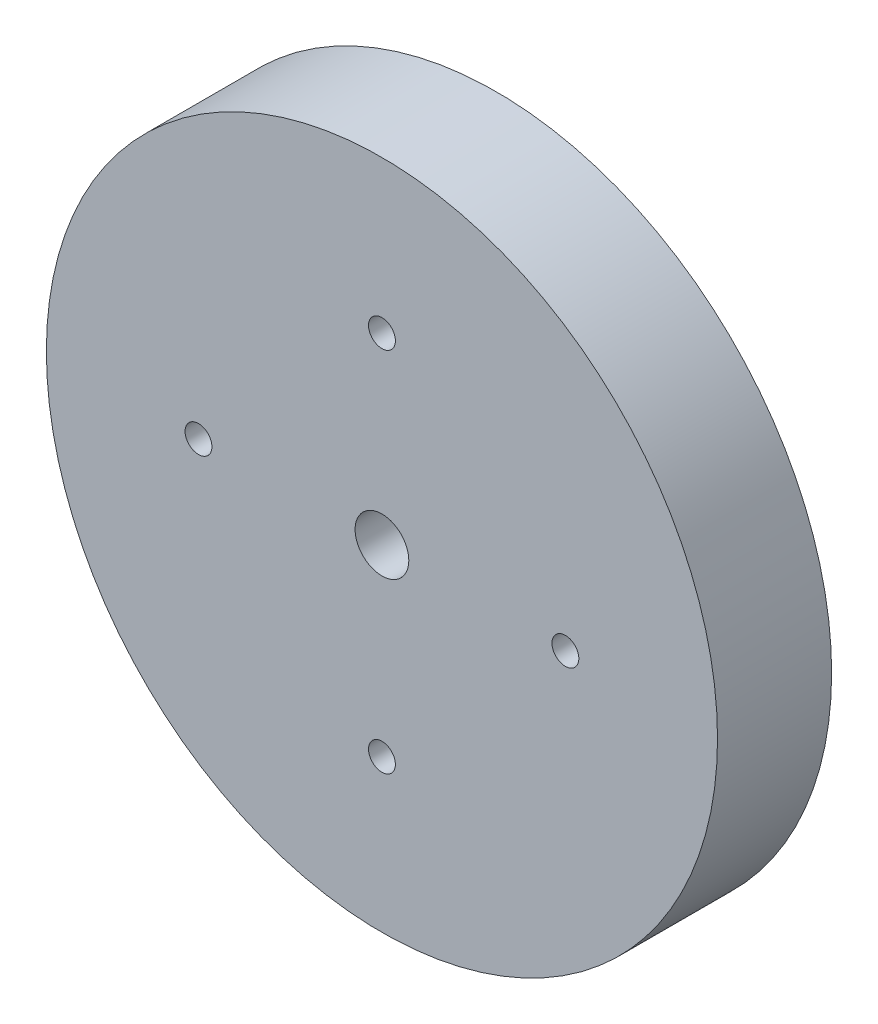
SolidWorks part; units mm, degrees
ref_plane "Front Plane" through (0, 0, 0) normal (0, 0, 1) x (1, 0, 0)
ref_plane "Top Plane" through (0, 0, 0) normal (0, 1, 0) x (1, 0, 0)
ref_plane "Right Plane" through (0, 0, 0) normal (1, 0, 0) x (0, 0, -1)
sketch "Sketch1" plane through (0, 0, 0) normal (0, 0, 1) x (1, 0, 0)
  line L0 (0, 0) -> (10.414, 0) construction
  line L1 (0, 0) -> (-10.414, 0) construction
  line L2 (0, 0) -> (0, 10.414) construction
  line L3 (0, 0) -> (0, -10.414) construction
  circle A0 centre (0, 0) radius 1.524
  circle A1 centre (0, 0) radius 19.05
  circle A3 centre (10.414, 0) radius 0.762
  circle A9 centre (-10.414, 0) radius 0.762
  circle A10 centre (0, 10.414) radius 0.762
  circle A11 centre (0, -10.414) radius 0.762
  point P12 (0, 0)
  dimension "D1" = 38.1
  dimension "D2" = 3.048
  dimension "D3" = 1.524
  dimension "D4" = 20.828
extrude "Boss-Extrude1" add sketch "Sketch1" along normal blind 6.477
